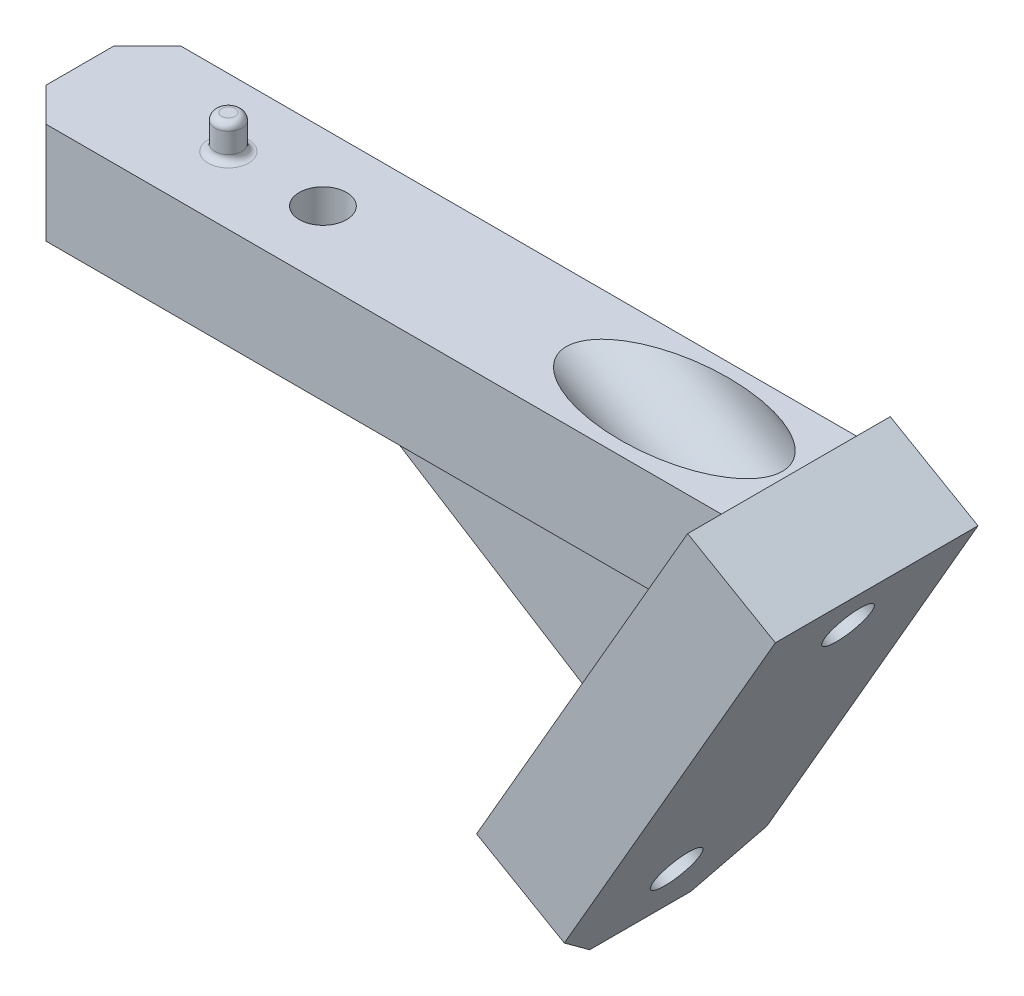
SolidWorks part; units mm, degrees
ref_plane "Front Plane" through (0, 0, 0) normal (0, 0, 1) x (1, 0, 0)
ref_plane "Top Plane" through (0, 0, 0) normal (0, 1, 0) x (1, 0, 0)
ref_plane "Right Plane" through (0, 0, 0) normal (1, 0, 0) x (0, 0, -1)
sketch "Sketch1" plane through (0, 0, 0) normal (0, 1, 0) x (1, 0, 0)
  line L1 (-52.5, 10) -> (52.5, 10)
  line L2 (-52.5, 10) -> (-52.5, -10)
  line L3 (-52.5, -10) -> (52.5, -10)
  line L4 (52.5, 10) -> (52.5, -10)
  line L5 (-52.5, 10) -> (52.5, -10) construction
  line L6 (-52.5, -10) -> (52.5, 10) construction
  point P0 (0, 0)
  dimension "D1" = 20
  dimension "D2" = 105
extrude "Boss-Extrude1" add sketch "Sketch1" along normal blind 15 contours L1 L4 L3 L2
sketch "Sketch2" plane through (0, 15, 0) normal (0, 1, 0) x (1, 0, 0)
  line L1 (-52.5, 10) -> (-52.5, -10) construction
  circle A0 centre (-16.5, 0) radius 3.5
  dimension "D2" = 7
  dimension "D1" = 36
extrude "Cut-Extrude1" cut sketch "Sketch2" against normal blind 15
sketch "Sketch3" plane through (0, 15, 0) normal (0, 1, 0) x (1, 0, 0)
  circle A0 centre (-30.5, 0) radius 2
  circle A1 centre (-16.5, 0) radius 3.5 construction
  dimension "D1" = 4
  dimension "D2" = 14
extrude "Boss-Extrude2" add sketch "Sketch3" along normal blind 5
sketch "Sketch4" plane through (0, 0, 0) normal (0, -1, 0) x (1, 0, 0)
  circle A0 centre (-16.5, 0) radius 5
  dimension "D1" = 10
extrude "Cut-Extrude2" cut sketch "Sketch4" against normal blind 8
sketch "Sketch5" plane through (0, 0, 0) normal (0, 0, 1) x (1, 0, 0)
  line L0 (52.5, 15) -> (52.5, -17.0975) construction
  line L1 (52.5, 15) -> (17.5, -45.6218)
  line L2 (17.5, -45.6218) -> (30.4904, -53.1218)
  line L3 (30.4904, -53.1218) -> (65.4904, 7.5)
  line L4 (65.4904, 7.5) -> (52.5, 15)
  dimension "D1" = 30
  dimension "D2" = 70
  dimension "D3" = 15
extrude "Boss-Extrude3" add sketch "Sketch5" along normal blind 15 and the other way blind 15
sketch "Sketch7" plane through (0, 0, 0) normal (0, 0, 1) x (1, 0, 0)
  line L0 (-8.0839, 0) -> (43.8397, 0)
  line L1 (43.8397, 0) -> (30, -23.9711)
  line L2 (52.5, 15) -> (17.5, -45.6218) construction
  line L3 (30, -23.9711) -> (-8.0839, 0)
  line L4 (52.5, 15) -> (17.5, -45.6218) construction
  point P0 (0, 0)
  dimension "D1" = 25
  dimension "D2" = 45
extrude "Boss-Extrude4" add sketch "Sketch7" along normal blind 5 and the other way blind 5 contours L0 L1 L3
sketch "Sketch8" plane through (32.8798, -18.9832, 0) normal (-0.866, 0.5, 0) x (0, 0, 1)
  circle A0 centre (0, -20) radius 3.5
  dimension "D1" = 7
  dimension "D2" = 20
extrude "Cut-Extrude3" cut sketch "Sketch8" against normal through all
chamfer "Chamfer2" distance 7.5 angle 45 2 edges at (23.9952, -49.3718, 15) (23.9952, -49.3718, -15)
fillet "Fillet8" radius 1 1 edges at (-30.5, 20, 2)
fillet "Fillet9" radius 1 1 edges at (-30.5, 15, 2)
chamfer "Chamfer4" distance 2 angle 45 1 edges at (-16.5, 0, -5)
chamfer "Chamfer5" distance 5 angle 45 2 edges at (-52.5, 7.5, -10) (-52.5, 7.5, 10)
sketch "Sketch9" plane through (32.8798, -18.9832, 0) normal (-0.866, 0.5, 0) x (0, 0, 1)
  circle A0 centre (0, 30.7567) radius 3.5
  dimension "D1" = 7
extrude "Cut-Extrude4" cut sketch "Sketch9" against normal through all both and the other way through all
sketch "Sketch11" plane through (32.8798, -18.9832, 0) normal (-0.866, 0.5, 0) x (0, 0, 1)
  circle A0 centre (0, 30.7567) radius 8
  dimension "D1" = 16
extrude "Cut-Extrude5" cut sketch "Sketch11" along normal blind 30
sketch "Sketch12" plane through (0, 0, 0) normal (0, 0, 1) x (1, 0, 0)
  line L1 (-78.9, 15) -> (46.5, 15) construction
  line L2 (-78.9, 15) -> (-78.9, 38) construction
  line L3 (-78.9, 38) -> (46.5, 38) construction
  line L4 (46.5, 15) -> (46.5, 38) construction
  line L5 (-47.5, 15) -> (52.5, 15) construction
  line L7 (-30.5, 19) -> (-30.5, -9.2819) construction
  line L8 (-32.5, 19) -> (-28.5, 19) construction
  line L10 (46.5, 38) -> (88.6793, 13.6478) construction
  line L11 (65.4904, 7.5) -> (52.5, 15) construction
  line L12 (-78.9, 18.5) -> (20.1238, 18.5) construction
  line L13 (-78.9, 38) -> (-52.9, 38) construction
  line L14 (-78.9, 38) -> (-78.9, -1) construction
  line L15 (-78.9, -1) -> (-52.9, -1) construction
  line L16 (-52.9, 38) -> (-52.9, -1) construction
  line L17 (-78.9, 18.5) -> (42.0116, -51.3084) construction
  line L18 (34.2404, -46.6266) -> (65.4904, 7.5) construction
  point P18 (42.0116, -51.3084)
  dimension "D1" = 125.4
  dimension "D2" = 77
  dimension "D3" = 23
  dimension "D4" = 16.9186
  dimension "D5" = 39
  dimension "D6" = 26
  dimension "D7" = 19.5
  dimension "D8" = 130.5457
